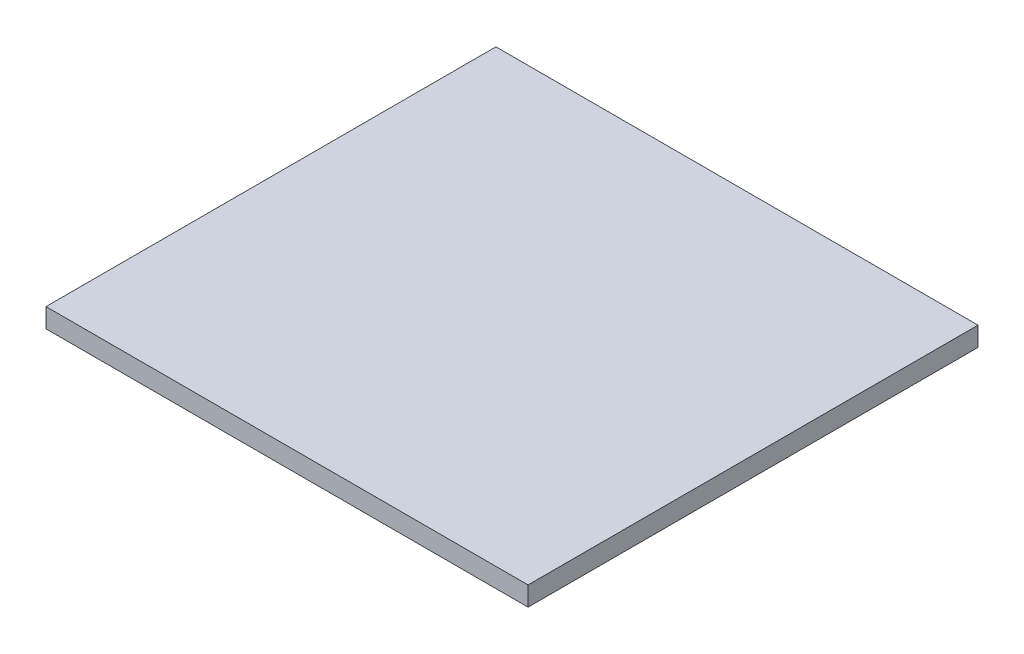
SolidWorks part; units mm, degrees
ref_plane "Front Plane" through (0, 0, 0) normal (0, 0, 1) x (1, 0, 0)
ref_plane "Top Plane" through (0, 0, 0) normal (0, 1, 0) x (1, 0, 0)
ref_plane "Right Plane" through (0, 0, 0) normal (1, 0, 0) x (0, 0, -1)
sketch "Sketch1" plane through (0, 0, 0) normal (0, 1, 0) x (1, 0, 0)
  line L1 (-75, 70) -> (75, 70)
  line L2 (-75, 70) -> (-75, -70)
  line L3 (-75, -70) -> (75, -70)
  line L4 (75, 70) -> (75, -70)
  line L5 (-75, 70) -> (75, -70) construction
  line L6 (-75, -70) -> (75, 70) construction
  point P0 (0, 0)
  dimension "D1" = 150
  dimension "D2" = 140
extrude "Boss-Extrude1" add sketch "Sketch1" along normal blind 6
